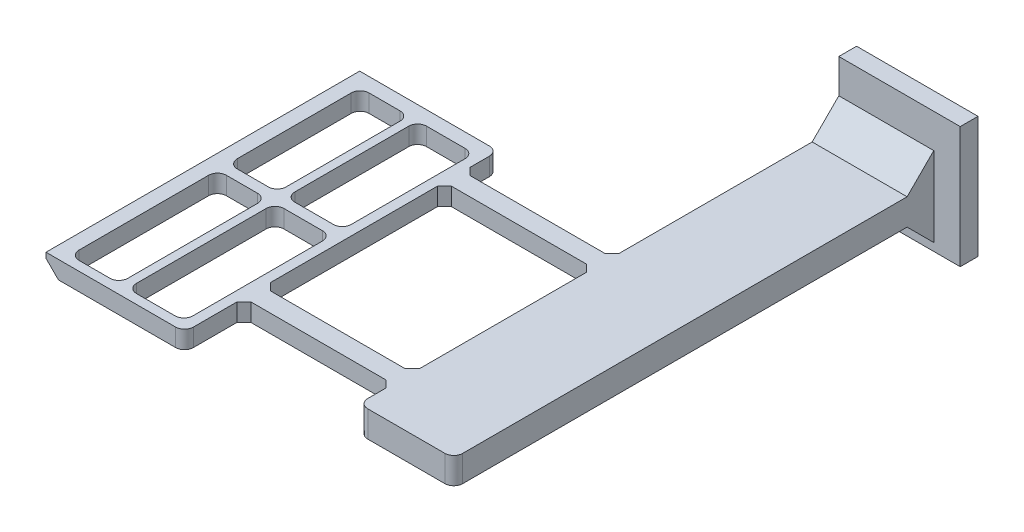
SolidWorks part; units mm, degrees
ref_plane "前视基准面" through (0, 0, 0) normal (0, 0, 1) x (1, 0, 0)
ref_plane "上视基准面" through (0, 0, 0) normal (0, 1, 0) x (1, 0, 0)
ref_plane "右视基准面" through (0, 0, 0) normal (1, 0, 0) x (0, 0, -1)
other "Configuration Table"
sketch "草图1" plane through (0, 0, 0) normal (0, 0, 1) x (1, 0, 0)
  line L0 (-66.9427, 36.5) -> (-67.6499, 35.7929) construction
  line L1 (-67.2963, 36.1464) -> (0.9966, 36.1464)
  line L2 (-67.2963, 36.1464) -> (-67.2963, -32.1464)
  line L3 (-67.2963, -32.1464) -> (0.9966, -32.1464)
  line L4 (0.9966, 36.1464) -> (0.9966, -32.1464)
  line L5 (0.643, -32.5) -> (1.3501, -31.7929) construction
extrude "凸台-拉伸1" add sketch "草图1" along normal blind 10
sketch "草图2" plane through (0, 0, 10) normal (0, 0, 1) x (1, 0, 0)
  line L0 (-67.2963, 36.1464) -> (-67.2963, -32.1464) construction
  line L1 (-13.8888, -12.7764) -> (-67.2963, -12.7764)
  line L2 (-13.8888, -12.7764) -> (-13.8888, 2)
  line L3 (-13.8888, 2) -> (-67.2963, 2)
  line L4 (-67.2963, -12.7764) -> (-67.2963, 2)
  point P4 (-67.2963, -5.6767)
  point P7 (-67.2963, 2)
extrude "凸台-拉伸2" add sketch "草图2" along normal blind 270
sketch "草图4" plane through (0, 2, 0) normal (0, 1, 0) x (1, 0, 0)
  line L0 (-67.2963, -280) -> (-67.2963, -10) construction
  line L1 (-67.2963, -260.8033) -> (-151.1637, -260.8033)
  line L2 (-67.2963, -260.8033) -> (-67.2963, -249.9352)
  line L3 (-67.2963, -249.9352) -> (-151.1637, -249.9352)
  line L4 (-151.1637, -260.8033) -> (-151.1637, -249.9352)
  line L6 (-151.6679, -249.9352) -> (-151.1637, -249.9352)
  line L10 (-67.2963, -137.6047) -> (-151.1637, -137.6047)
  line L11 (-67.2963, -137.6047) -> (-67.2963, -147.9898)
  line L12 (-67.2963, -147.9898) -> (-151.1637, -147.9898)
  line L13 (-151.1637, -137.6047) -> (-151.1637, -147.9898)
  line L14 (-151.1637, -294.2176) -> (-229.0829, -294.2176)
  line L15 (-151.1637, -294.2176) -> (-151.1637, -117.7517)
  line L16 (-151.1637, -117.7517) -> (-229.0829, -117.7517)
  line L17 (-229.0829, -294.2176) -> (-229.0829, -117.7517)
  line L19 (-220.8414, -240.52) -> (-220.8414, -288.9214)
  line L20 (-220.8414, -288.9214) -> (-156.7676, -288.9214)
  line L21 (-156.7676, -192.1185) -> (-156.7676, -288.9214)
  line L22 (-220.8414, -125.7537) -> (-156.7676, -125.7537)
  line L23 (-220.8414, -125.7537) -> (-220.8414, -240.52)
  line L25 (-156.7676, -125.7537) -> (-156.7676, -240.52)
  line L26 (-193.3639, -125.7537) -> (-188.4767, -125.7537)
  line L27 (-193.3639, -125.7537) -> (-193.3639, -288.9214)
  line L28 (-193.3639, -288.9214) -> (-188.4767, -288.9214)
  line L29 (-188.4767, -125.7537) -> (-188.4767, -288.9214)
  line L30 (-220.8414, -199.8528) -> (-156.7676, -199.8528)
  line L31 (-220.8414, -199.8528) -> (-220.8414, -205.9846)
  line L32 (-220.8414, -205.9846) -> (-156.7676, -205.9846)
  line L33 (-156.7676, -199.8528) -> (-156.7676, -205.9846)
  point P27 (-156.7676, -205.9846)
extrude "凸台-拉伸3" add sketch "草图4" against normal blind 10
chamfer "倒角1" distance 15 angle 45 2 edges at (-40.5926, -12.7764, 10) (-40.5926, 2, 10)
chamfer "倒角3" distance 7 angle 45 1 edges at (-229.0829, -8, 205.9846)
fillet "圆角3" radius 5 20 edges at (-13.8888, -5.3882, 280) (-67.2963, -5.3882, 280) (-220.8414, -3, 125.7537) (-220.8414, -3, 205.9846) (-193.3639, -3, 288.9214) (-220.8414, -3, 288.9214) (-156.7676, -3, 288.9214) (-156.7676, -3, 199.8528) (-188.4767, -3, 125.7537) (-156.7676, -3, 125.7537) (-193.3639, -3, 125.7537) (-151.1637, -3, 294.2176) (-151.1637, -3, 117.7517) (-193.3639, -3, 199.8528) (-156.7676, -3, 205.9846) (-193.3639, -3, 205.9846) (-220.8414, -3, 199.8528) (-188.4767, -3, 199.8528) (-188.4767, -3, 205.9846) (-188.4767, -3, 288.9214)
chamfer "倒角4" distance 4 angle 45 8 edges at (-67.2963, -3, 249.9352) (-67.2963, -3, 260.8033) (-151.1637, -3, 260.8033) (-151.1637, -3, 137.6047) (-67.2963, -3, 137.6047) (-67.2963, -3, 147.9898) (-151.1637, -3, 147.9898) (-151.1637, -3, 249.9352)
